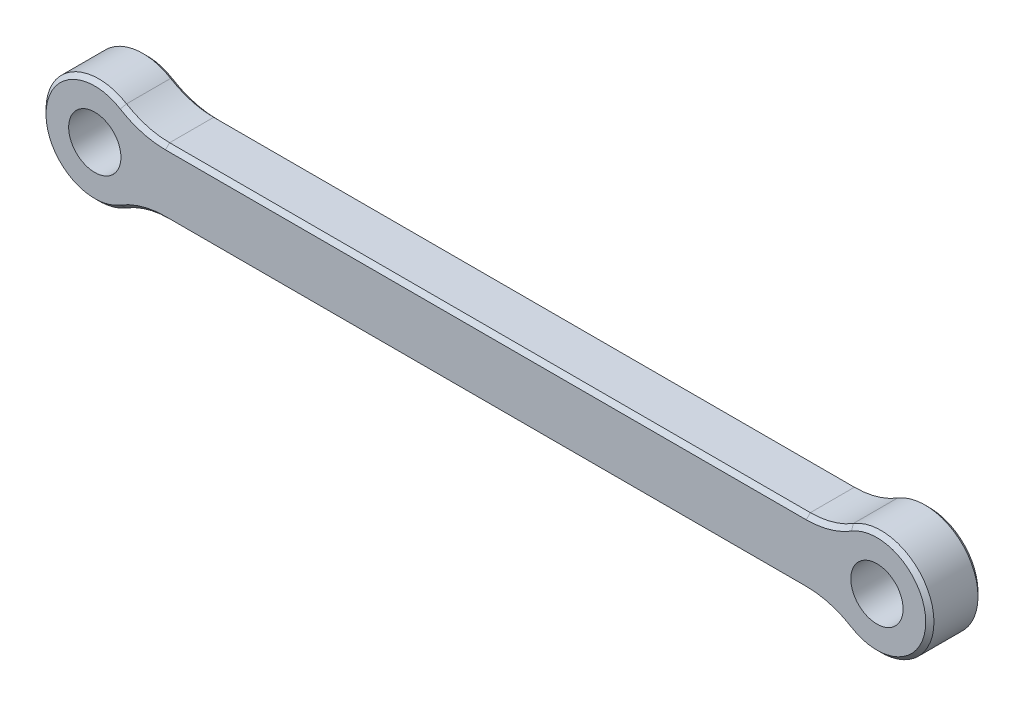
SolidWorks part; units mm, degrees
ref_plane "Front Plane" through (0, 0, 0) normal (0, 0, 1) x (1, 0, 0)
ref_plane "Top Plane" through (0, 0, 0) normal (0, 1, 0) x (1, 0, 0)
ref_plane "Right Plane" through (0, 0, 0) normal (1, 0, 0) x (0, 0, -1)
sketch "Sketch2" plane through (0, 0, 0) normal (0, 0, 1) x (1, 0, 0)
  line L0 (0, 0) -> (95, 0) construction
  line L5 (0, 0) -> (95, 0) construction
  line L6 (0, 4) -> (95, 4)
  line L7 (0, -4) -> (95, -4)
  circle A0 centre (0, 0) radius 6.425
  circle A5 centre (0, 0) radius 3.175
  circle A6 centre (95, 0) radius 3.175
  arc A7 (0, 4) -> (0, -4) centre (0, 0) ccw
  arc A8 (95, -4) -> (95, 4) centre (95, 0) ccw
  circle A9 centre (95, 0) radius 6.425
  point P17 (47.5, 0)
  dimension "D5" = 6.35
  dimension "D2" = 12.85
  dimension "D1" = 95
  dimension "D7" = 8
  dimension "D8" = 95
extrude "Boss-Extrude1" add sketch "Sketch2" along normal blind 6.35 contours A9 L6 A0 L7 | L6 A9 L7 A8 A6 | L7 A9 L6 A8 | L6 A7 L7 A0 A5 | A7 L6 A0 L7
fillet "Fillet1" radius 10 4 edges at (89.972, 4, 3.175) (89.972, -4, 3.175) (5.028, -4, 3.175) (5.028, 4, 3.175)
chamfer "Chamfer1" distance 0.5 angle 45 16 edges at (47.5, -4, 0) (47.5, -4, 6.35) (47.5, 4, 6.35) (47.5, 4, 0) (5.8726, -4.3762, 6.35) (5.8726, -4.3762, 0) (89.1274, -4.3762, 6.35) (89.1274, -4.3762, 0) (-6.425, 0, 0) (-6.425, 0, 6.35) (101.425, 0, 0) (101.425, 0, 6.35) (5.8726, 4.3762, 6.35) (5.8726, 4.3762, 0) (89.1274, 4.3762, 6.35) (89.1274, 4.3762, 0)
equation "\"D2@Sketch2\"=\"D5@Sketch2\"+6.5mm"
